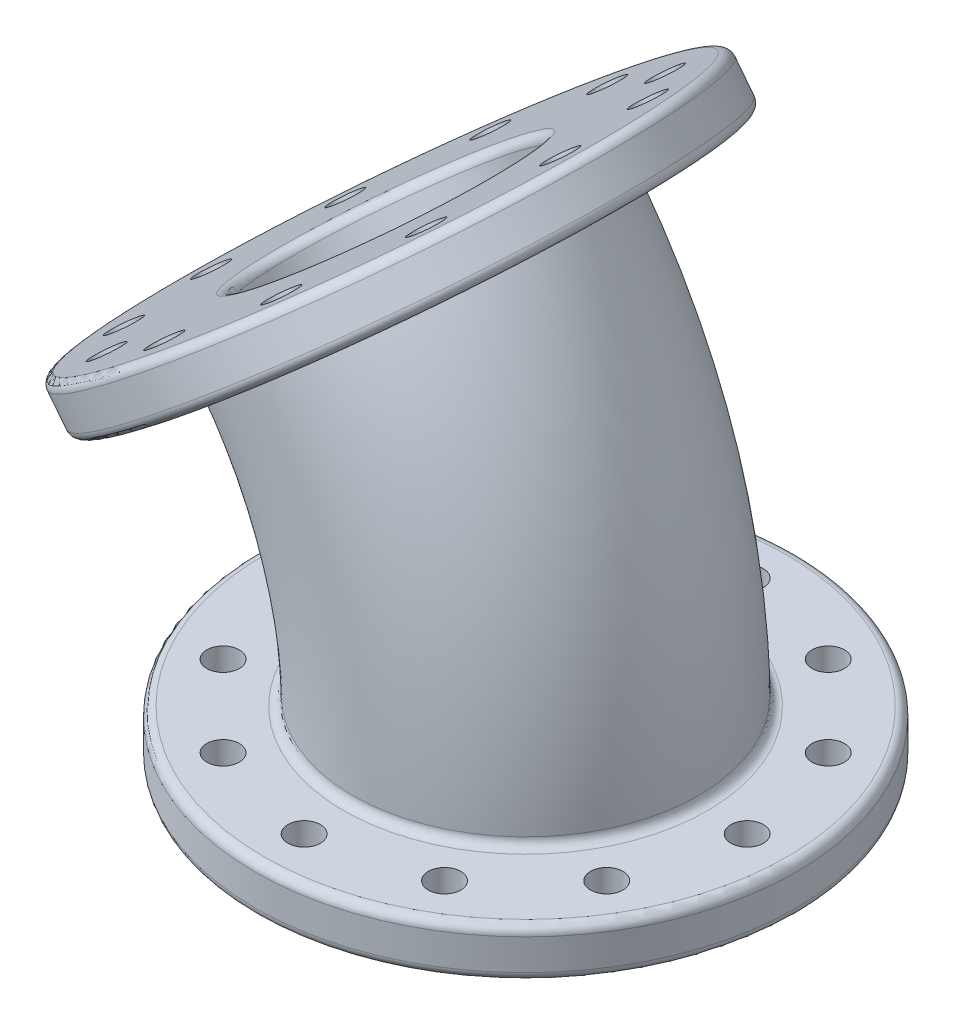
SolidWorks part; units mm, degrees
material "AISI 304"
ref_plane "Front Plane" through (0, 0, 0) normal (0, 0, 1) x (1, 0, 0)
ref_plane "Top Plane" through (0, 0, 0) normal (0, 1, 0) x (1, 0, 0)
ref_plane "Right Plane" through (0, 0, 0) normal (1, 0, 0) x (0, 0, -1)
sketch "Sketch2" plane through (0, 0, 0) normal (0, 1, 0) x (1, 0, 0)
  circle A0 centre (0, 0) radius 61
  circle A1 centre (0, 0) radius 28
  circle A2 centre (0, 50) radius 3.665
  circle A3 centre (25, 43.3013) radius 3.665
  circle A4 centre (43.3013, 25) radius 3.665
  circle A5 centre (50, 0) radius 3.665
  circle A6 centre (43.3013, -25) radius 3.665
  circle A7 centre (25, -43.3013) radius 3.665
  circle A8 centre (0, -50) radius 3.665
  circle A9 centre (-25, -43.3013) radius 3.665
  circle A10 centre (-43.3013, -25) radius 3.665
  circle A11 centre (-50, 0) radius 3.665
  circle A12 centre (-43.3013, 25) radius 3.665
  circle A13 centre (-25, 43.3013) radius 3.665
  dimension "D1" = 56
  dimension "D2" = 33
  dimension "D3" = 11
  dimension "D4" = 7.33
  dimension "D5" = 12
extrude "Boss-Extrude1" add sketch "Sketch2" along normal blind 11
sketch "Sketch3" plane through (0, 11, 0) normal (0, 1, 0) x (1, 0, 0)
  line L0 (-117, -68.8683) -> (-117, 50) construction
  circle A0 centre (0, 0) radius 28
  circle A1 centre (0, 0) radius 39
  circle A2 centre (0, 0) radius 28 construction
  point P8 (-106, 75.8036)
  point P9 (-106, 54.6112)
  point P10 (0, 0)
  point P11 (-117, 0)
  point P12 (-117, -68.8683)
  point P13 (19.4586, -3.4746)
  dimension "D1" = 11
  dimension "D2" = 117
revolve "Revolve1" add sketch "Sketch3" angle 38 about L0
sketch "Sketch7" plane through (-49.6842, 63.5929, 0) normal (-0.6157, 0.788, 0) x (0.788, 0.6157, 0)
  circle A0 centre (31.575, 0) radius 28
  circle A1 centre (31.575, 0) radius 61
  circle A2 centre (31.575, 50) radius 3.665
  circle A4 centre (31.575, 0) radius 28 construction
  circle A5 centre (56.575, 43.3013) radius 3.665
  circle A6 centre (74.8763, 25) radius 3.665
  circle A7 centre (81.575, 0) radius 3.665
  circle A8 centre (74.8763, -25) radius 3.665
  circle A9 centre (56.575, -43.3013) radius 3.665
  circle A10 centre (31.575, -50) radius 3.665
  circle A11 centre (6.575, -43.3013) radius 3.665
  circle A12 centre (-11.7263, -25) radius 3.665
  circle A13 centre (-18.425, 0) radius 3.665
  circle A14 centre (-11.7263, 25) radius 3.665
  circle A15 centre (6.575, 43.3013) radius 3.665
  dimension "D1" = 33
  dimension "D3" = 7.33
  dimension "D2" = 11
  dimension "D4" = 12
extrude "Boss-Extrude2" add sketch "Sketch7" along normal blind 11
fillet "Fillet1" radius 2 8 edges at (-53.6393, 74.462, 0) (0, 0, 28) (0, 0, 61) (0, 11, 61) (0, 11, 39) (-24.8027, 83.0324, 39) (-72.8714, 45.477, 0) (-79.6437, 54.1452, 0)
